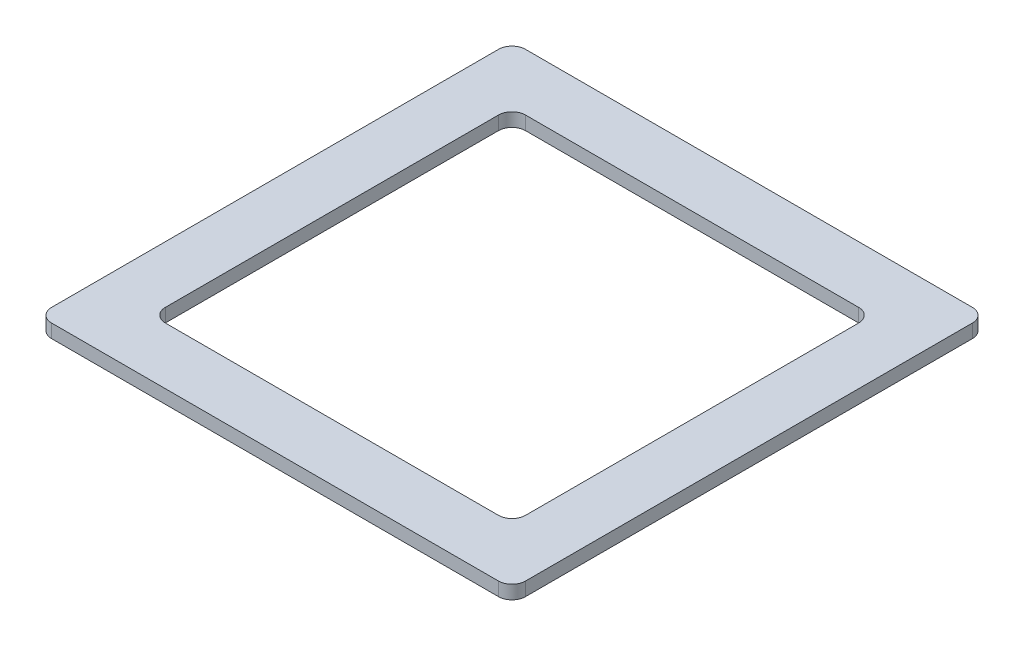
SolidWorks part; units mm, degrees
ref_plane "Front Plane" through (0, 0, 0) normal (0, 0, 1) x (1, 0, 0)
ref_plane "Top Plane" through (0, 0, 0) normal (0, 1, 0) x (1, 0, 0)
ref_plane "Right Plane" through (0, 0, 0) normal (1, 0, 0) x (0, 0, -1)
sketch "Sketch1" plane through (0, 0, 0) normal (0, 1, 0) x (1, 0, 0)
  line L1 (-175, -175) -> (175, -175)
  line L2 (-175, -175) -> (-175, 175)
  line L3 (-175, 175) -> (175, 175)
  line L4 (175, -175) -> (175, 175)
  line L5 (-175, -175) -> (175, 175) construction
  line L6 (-175, 175) -> (175, -175) construction
  point P0 (0, 0)
  dimension "D1" = 350
  dimension "D2" = 350
extrude "Boss-Extrude1" add sketch "Sketch1" along normal blind 10
sketch "Sketch2" plane through (0, 10, 0) normal (0, 1, 0) x (1, 0, 0)
  line L0 (-175, 175) -> (-175, -175) construction
  line L1 (-133, -133) -> (133, -133)
  line L2 (-133, -133) -> (-133, 133)
  line L3 (-133, 133) -> (133, 133)
  line L4 (133, -133) -> (133, 133)
  line L5 (-133, -133) -> (133, 133) construction
  line L6 (-133, 133) -> (133, -133) construction
  line L7 (175, 175) -> (-175, 175) construction
  point P0 (0, 0)
  dimension "D1" = 42
  dimension "D2" = 42
extrude "Cut-Extrude1" cut sketch "Sketch2" against normal through all
fillet "Fillet1" radius 10 8 edges at (-133, 5, -133) (175, 5, -175) (-133, 5, 133) (133, 5, 133) (175, 5, 175) (133, 5, -133) (-175, 5, -175) (-175, 5, 175)
